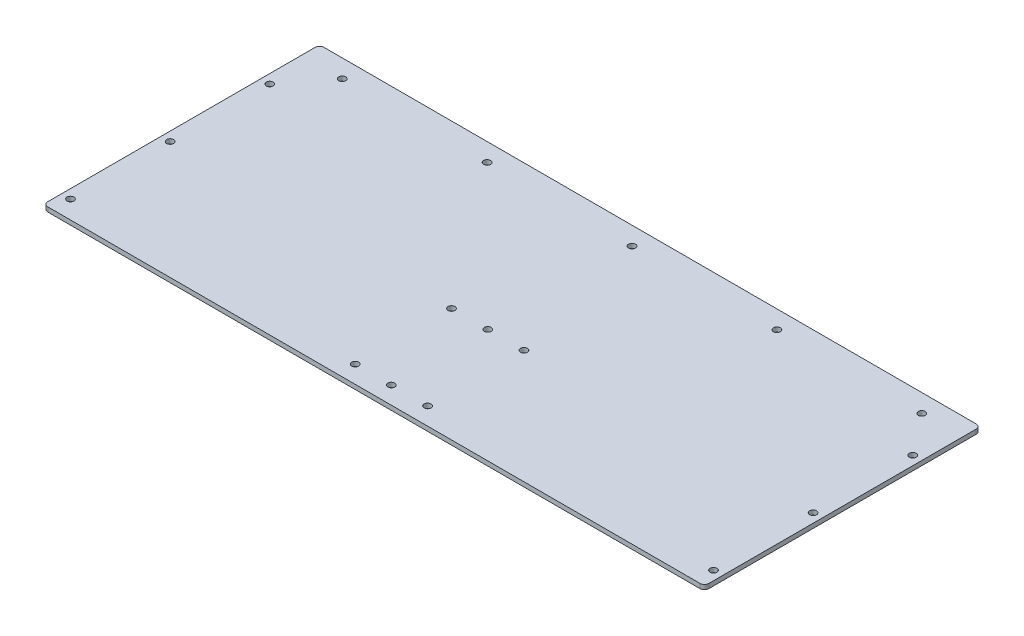
SolidWorks part; units mm, degrees
material "5052-H32"
ref_plane "Front" through (0, 0, 0) normal (0, 0, 1) x (1, 0, 0)
ref_plane "Top" through (0, 0, 0) normal (0, 1, 0) x (1, 0, 0)
ref_plane "Right" through (0, 0, 0) normal (1, 0, 0) x (0, 0, -1)
sketch "Sketch1" plane through (0, 0, 0) normal (0, 1, 0) x (1, 0, 0)
  line L0 (231.775, 0) -> (231.775, 46.0375) construction
  line L1 (0, 0) -> (463.55, 0)
  line L2 (0, 0) -> (0, 193.675)
  line L3 (0, 193.675) -> (463.55, 193.675)
  line L4 (463.55, 0) -> (463.55, 193.675)
  line L5 (231.775, 46.0375) -> (253.2062, 46.0375) construction
  line L6 (206.375, 12.2555) -> (257.175, 12.2555) construction
  line L7 (206.375, 79.8195) -> (257.175, 79.8195) construction
  line L8 (231.775, 193.675) -> (231.775, 180.975) construction
  circle A0 centre (231.775, 46.0375) radius 21.4312 construction
  circle A1 centre (231.775, 12.2555) radius 2.4257
  circle A2 centre (257.175, 12.2555) radius 2.4257
  circle A3 centre (206.375, 12.2555) radius 2.4257
  circle A4 centre (257.175, 79.8195) radius 2.4257
  circle A5 centre (231.775, 79.8195) radius 2.4257
  circle A6 centre (206.375, 79.8195) radius 2.4257
  circle A7 centre (231.775, 180.975) radius 2.4257
  circle A8 centre (333.375, 180.975) radius 2.4257
  circle A9 centre (434.975, 180.975) radius 2.4257
  circle A12 centre (28.575, 180.975) radius 2.4257
  circle A13 centre (130.175, 180.975) radius 2.4257
  dimension "D3" = 42.8625
  dimension "D5" = 4.8514
  dimension "D9" = 4.8514
  dimension "D1" = 463.55
  dimension "D2" = 193.675
  dimension "D4" = 46.0375
  dimension "D6" = 33.782
  dimension "D7" = 25.4
  dimension "D8" = 12.7
  dimension "D11" = 101.6
  dimension "D10" = 3
extrude "Boss-Extrude1" add sketch "Sketch1" along normal blind 3.175
sketch "Sketch2" plane through (0, 3.175, 0) normal (0, 1, 0) x (1, 0, 0)
  line L0 (0, 193.675) -> (0, 0) construction
  line L1 (0, 0) -> (463.55, 0) construction
  line L2 (231.775, 193.675) -> (231.775, -51.395) construction
  line L3 (463.55, 193.675) -> (0, 193.675) construction
  circle A0 centre (6.35, 12.7) radius 2.4257
  circle A1 centre (6.35, 82.55) radius 2.4257
  circle A2 centre (6.35, 152.4) radius 2.4257
  circle A3 centre (6.35, 222.25) radius 2.4257
  circle A4 centre (457.2, 222.25) radius 2.4257
  circle A5 centre (457.2, 152.4) radius 2.4257
  circle A6 centre (457.2, 82.55) radius 2.4257
  circle A7 centre (457.2, 12.7) radius 2.4257
  dimension "D3" = 4.8514
  dimension "D1" = 6.35
  dimension "D2" = 12.7
  dimension "D5" = 69.85
  dimension "D4" = 4
extrude "Cut-Extrude1" cut sketch "Sketch2" against normal through all
fillet "Fillet1" radius 3.175 4 edges at (0, 1.5875, -193.675) (463.55, 1.5875, -193.675) (463.55, 1.5875, 0) (0, 1.5875, 0)
